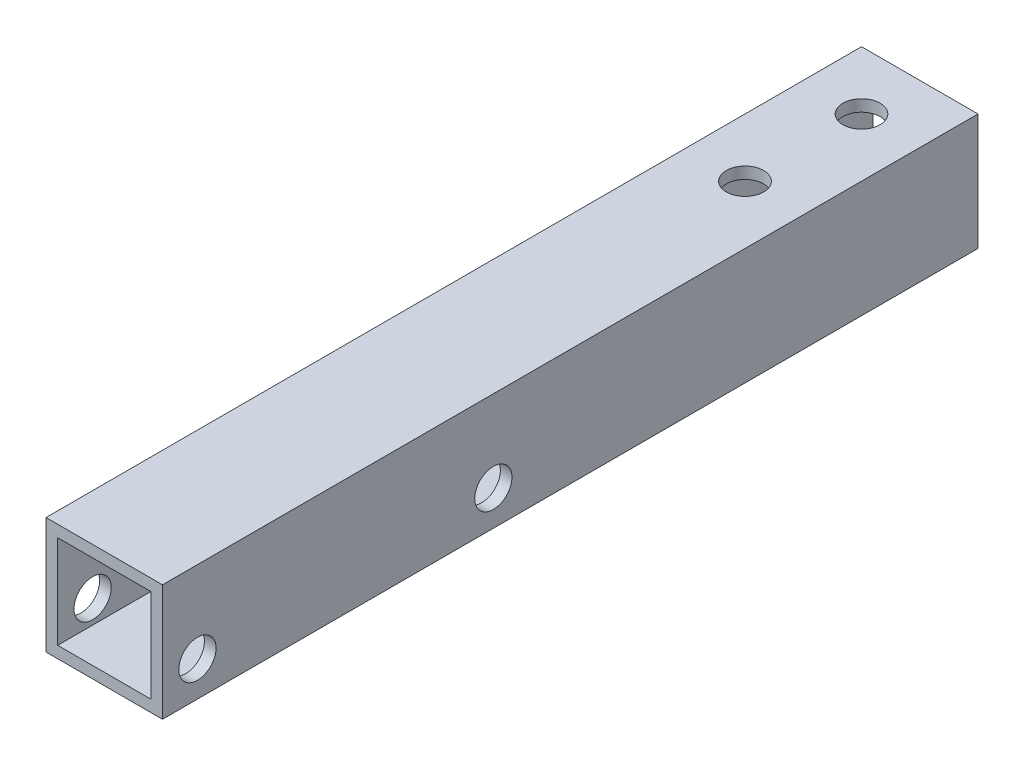
SolidWorks part; units mm, degrees
material "5052-H34"
ref_plane "正面" through (0, 0, 0) normal (0, 0, 1) x (1, 0, 0)
ref_plane "平面" through (0, 0, 0) normal (0, 1, 0) x (1, 0, 0)
ref_plane "右側面" through (0, 0, 0) normal (1, 0, 0) x (0, 0, -1)
sketch "ｽｹｯﾁ1" plane through (0, 0, 0) normal (0, 0, 1) x (1, 0, 0)
  line L1 (5, 5) -> (-5, 5)
  line L2 (5, 5) -> (5, -5)
  line L3 (5, -5) -> (-5, -5)
  line L4 (-5, 5) -> (-5, -5)
  line L5 (5, 5) -> (-5, -5) construction
  line L6 (5, -5) -> (-5, 5) construction
  point P0 (0, 0)
  dimension "D1" = 10
extrude "押し出し-薄板1" add sketch "ｽｹｯﾁ1" along normal blind 70 thin thin type one direction reverse wall 1
sketch "ｽｹｯﾁ3" plane through (0, 5, 0) normal (0, 1, 0) x (1, 0, 0)
  line L0 (0, 0) -> (0, -70) construction
  line L1 (5, -70) -> (-5, -70) construction
  line L2 (5, 0) -> (-5, 0) construction
  circle A0 centre (0, -5) radius 1.6
  circle A1 centre (0, -15) radius 1.6
  dimension "D1" = 3.2
  dimension "D2" = 10
  dimension "D3" = 3.2
  dimension "D4" = 5
extrude "ｶｯﾄ - 押し出し2" cut sketch "ｽｹｯﾁ3" against normal through all and the other way through all
sketch "ｽｹｯﾁ4" plane through (-5, 0, 0) normal (-1, 0, 0) x (0, 0, 1)
  line L0 (0, -2) -> (70, -2) construction
  line L1 (0, 5) -> (0, -5) construction
  line L2 (70, 5) -> (70, -5) construction
  line L3 (70, -5) -> (0, -5) construction
  circle A0 centre (67, -2) radius 1.6
  circle A1 centre (41.6, -2) radius 1.6
  dimension "D2" = 25.4
  dimension "D3" = 3.2
  dimension "D4" = 3
  dimension "D5" = 3.2
  dimension "D1" = 3
extrude "ｶｯﾄ - 押し出し3" cut sketch "ｽｹｯﾁ4" against normal through all
